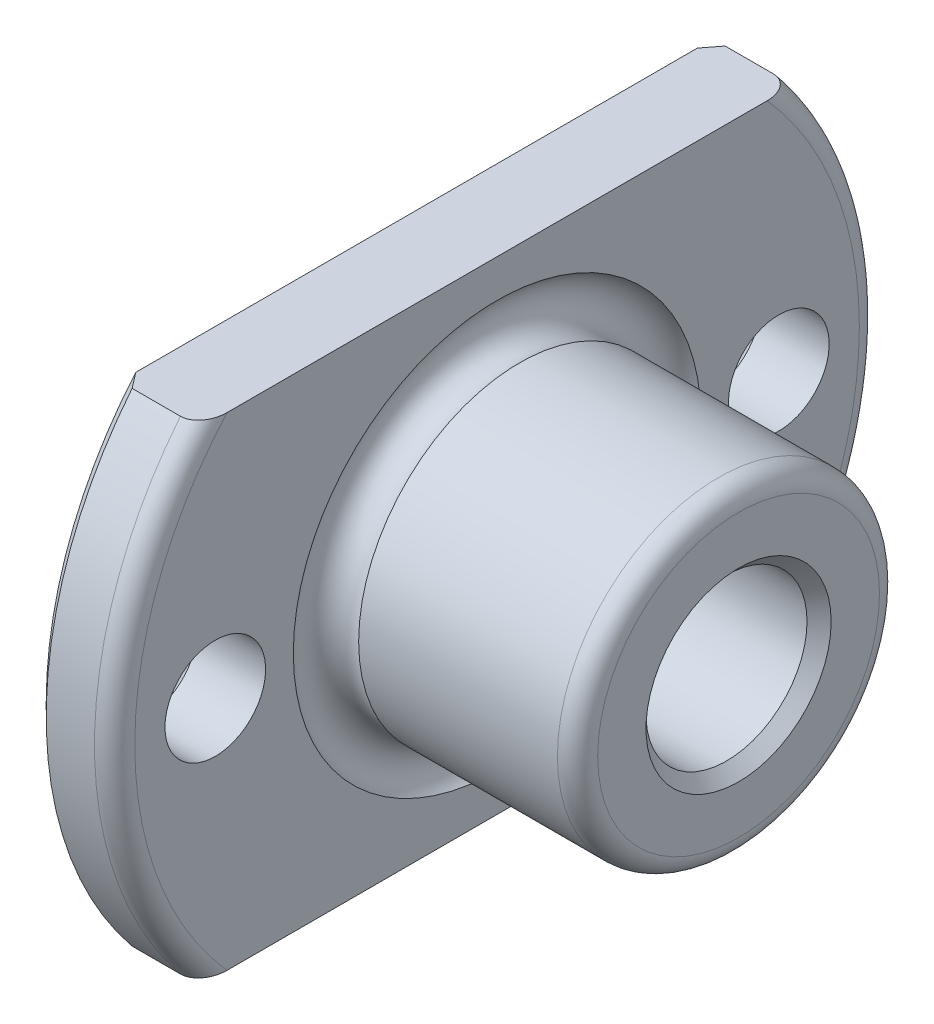
SolidWorks part; units mm, degrees
material "CA"
ref_plane "Face" through (0, 0, 0) normal (0, 0, 1) x (1, 0, 0)
ref_plane "Dessus" through (0, 0, 0) normal (0, 1, 0) x (1, 0, 0)
ref_plane "Droite" through (0, 0, 0) normal (1, 0, 0) x (0, 0, -1)
sketch "Esquisse1" plane through (0, 0, 0) normal (0, 0, 1) x (1, 0, 0)
  line L0 (0, 2) -> (8, 2)
  line L1 (8, 2) -> (8, 3.5)
  line L2 (7.5, 4) -> (2.5615, 4)
  line L3 (2, 5.0615) -> (2, 9)
  line L4 (1.5, 9.5) -> (0, 9.5)
  line L5 (0, 9.5) -> (0, 2)
  line L6 (0, 0) -> (6, 0) construction
  arc A0 (2, 9) -> (1.5, 9.5) centre (1.5, 9) ccw
  arc A1 (8, 3.5) -> (7.5, 4) centre (7.5, 3.5) ccw
  arc A3 (2, 5.0615) -> (2.5615, 4) centre (2.2807, 4.5307) ccw
  point P11 (2, 9.5)
  point P14 (8, 4)
  dimension "D6" = 0.5
  dimension "D1" = 2
  dimension "D2" = 4
  dimension "D3" = 9.5
  dimension "D4" = 8
  dimension "D5" = 2
revolve "Révolution1" add sketch "Esquisse1" angle 360 about L6
hole_wizard "Trou taraudé M3x0.51" positions "Esquisse3" profile "Esquisse2" tap size "M3x0.5" standard "Ansi Métrique" end condition through all
sketch "Esquisse3" plane through (0, 0, 0) normal (-1, 0, 0) x (0, 0, 1)
  line L0 (-9.3525, 0) -> (10.4748, 0) construction
  circle A0 centre (0, 0) radius 2 construction
  point P0 (-7, 0)
  point P1 (7, 0)
  dimension "D1" = 14
  dimension "D2" = 7
  dimension "D3" = 7
cosmetic thread "Représentation de filetage1" parameters "D2"=3
cosmetic thread "Représentation de filetage2" parameters "D2"=3
sketch "Esquisse2" plane through (0, 0, -7) normal (0, 1, 0) x (0, 0, 1)
  line L0 (0, 0) -> (0, 8)
  line L1 (0, 8) -> (1.6, 8)
  line L2 (1.25, 7.65) -> (1.25, 0)
  line L5 (1.25, 0) -> (0, 0)
  line L7 (1.6, 8) -> (1.25, 7.65)
  line L8 (-1.6, 8) -> (-1.25, 7.65) construction
  line L11 (0, -6.35) -> (0, 107.95) construction
  dimension "Diamètre du trou pour taraudage jusqu'au prochain" = 2.5
  dimension "Profondeur du trou pour taraudage jusqu'au prochain" = 8
  dimension "Diamètre du fraisage débouchant" = 3.2
  dimension "Angle du fraisage débouchant" = 90
chamfer "Chanfrein1" distance 0.3 angle 45 5 edges at (0, 0, 2) (0, 0, 9.5) (8, 0, 2) (0, 0, -5.75) (0, 0, 8.25)
sketch "Esquisse6" plane through (0, 0, 0) normal (-1, 0, 0) x (0, 0, 1)
  line L0 (7, 0) -> (-21.5692, 0) construction
sketch "Esquisse7" plane through (0, 0, 0) normal (1, 0, 0) x (0, 0, -1)
  line L1 (10, 6) -> (-10, 6)
  line L2 (10, 6) -> (10, -6)
  line L3 (10, -6) -> (-10, -6)
  line L4 (-10, 6) -> (-10, -6)
  line L5 (10, 6) -> (-10, -6) construction
  line L6 (10, -6) -> (-10, 6) construction
  line L7 (-13.1633, -10.9733) -> (13.1633, -10.9733)
  line L8 (-13.1633, -10.9733) -> (-13.1633, 10.9733)
  line L9 (-13.1633, 10.9733) -> (13.1633, 10.9733)
  line L10 (13.1633, -10.9733) -> (13.1633, 10.9733)
  line L11 (-13.1633, -10.9733) -> (13.1633, 10.9733) construction
  line L12 (-13.1633, 10.9733) -> (13.1633, -10.9733) construction
  point P0 (0, 0)
  point P6 (0, 0)
  point P7 (0, 0)
  dimension "D1" = 12
  dimension "D2" = 20
extrude "Enlèv. mat.-Extru.2" cut sketch "Esquisse7" along normal blind 10
